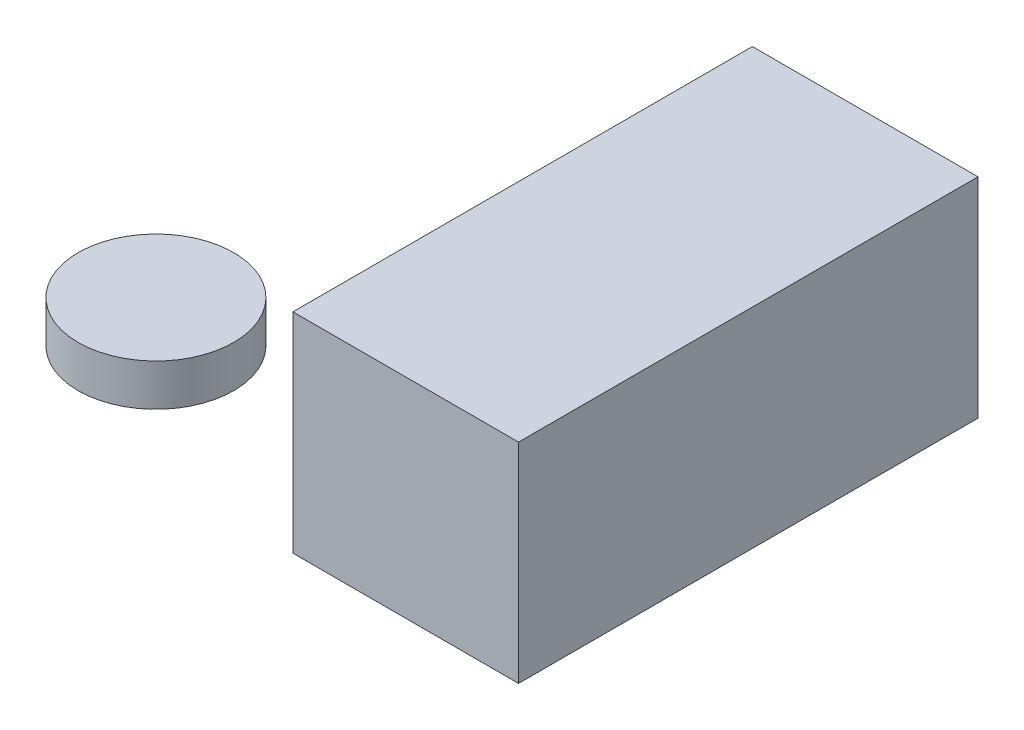
SolidWorks part; units mm, degrees
ref_plane "前视基准面" through (0, 0, 0) normal (0, 0, 1) x (1, 0, 0)
ref_plane "上视基准面" through (0, 0, 0) normal (0, 1, 0) x (1, 0, 0)
ref_plane "右视基准面" through (0, 0, 0) normal (1, 0, 0) x (0, 0, -1)
sketch "草图2" plane through (0, 0, 0) normal (0, 1, 0) x (1, 0, 0)
  line L1 (-26.9852, -54.9566) -> (26.9852, -54.9566)
  line L2 (-26.9852, -54.9566) -> (-26.9852, 54.9566)
  line L3 (-26.9852, 54.9566) -> (26.9852, 54.9566)
  line L4 (26.9852, -54.9566) -> (26.9852, 54.9566)
  line L5 (-26.9852, -54.9566) -> (26.9852, 54.9566) construction
  line L6 (-26.9852, 54.9566) -> (26.9852, -54.9566) construction
  point P0 (0, 0)
extrude "凸台-拉伸1" add sketch "草图2" along normal blind 50
sketch "草图3" plane through (0, 0, 0) normal (0, 1, 0) x (1, 0, 0)
  line L1 (-56.9852, 0) -> (0, 0) construction
  line L2 (-26.9852, 54.9566) -> (-26.9852, -54.9566) construction
  circle A0 centre (-56.9852, 0) radius 5
  dimension "D1" = 10
  dimension "D2" = 30
extrude "凸台-拉伸2" add sketch "草图3" along normal blind 10 separate body contours A0
cosmetic thread "装饰螺纹线1" parameters "D2"=8.376
sketch "草图4" plane through (0, 0, 0) normal (0, 1, 0) x (1, 0, 0)
  circle A0 centre (-86.3368, -28.3774) radius 18.6143
extrude "凸台-拉伸3" add sketch "草图4" along normal blind 10 separate body
